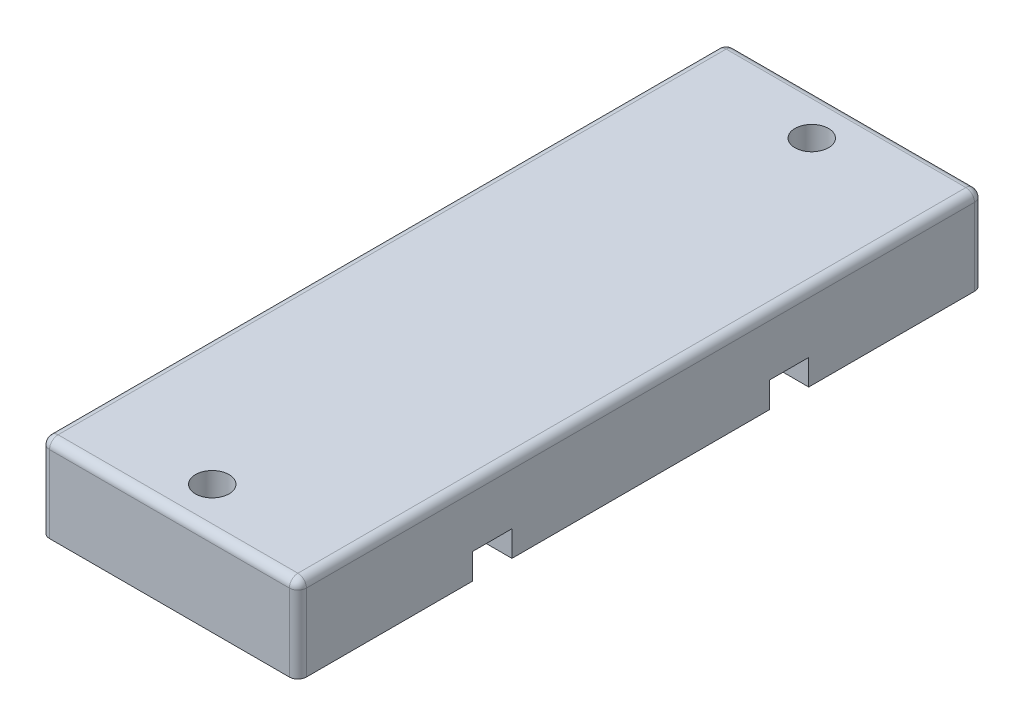
SolidWorks part; units mm, degrees
material "ABS PC"
ref_plane "Front Plane" through (0, 0, 0) normal (0, 0, 1) x (1, 0, 0)
ref_plane "Top Plane" through (0, 0, 0) normal (0, 1, 0) x (1, 0, 0)
ref_plane "Right Plane" through (0, 0, 0) normal (1, 0, 0) x (0, 0, -1)
sketch "Sketch1" plane through (0, 0, 0) normal (0, 1, 0) x (1, 0, 0)
  line L4 (0, 101.6) -> (38.1, 101.6)
  line L5 (0, 101.6) -> (0, 117.8149) construction
  line L6 (38.1, 117.8149) -> (38.1, -40.9351) construction
  line L7 (38.1, 101.6) -> (38.1, 0)
  line L8 (38.1, 0) -> (0, 0)
  line L9 (0, 0) -> (0, 101.6)
extrude "Boss-Extrude1" add sketch "Sketch1" along normal blind 12.7
sketch "Sketch9" plane through (0, 12.7, 0) normal (0, 1, 0) x (1, 0, 0)
  line L0 (19.05, 0) -> (19.05, 6.35) construction
  line L1 (0, 0) -> (38.1, 0) construction
  line L2 (19.05, 101.6) -> (19.05, 95.25) construction
  line L3 (38.1, 101.6) -> (0, 101.6) construction
sketch "Sketch12" plane through (0, 0, 0) normal (-1, 0, 0) x (0, 0, 1)
  line L0 (-101.6, 0) -> (-75.7538, 0) construction
  line L1 (-101.6, 0) -> (0, 0) construction
  line L2 (-75.7538, 0) -> (-69.9156, 0) construction
  line L3 (-69.9156, 0) -> (-31.741, 0) construction
  line L4 (-31.741, 0) -> (-25.9028, 0) construction
  line L5 (-75.7538, 0) -> (-75.7538, 3.81)
  line L6 (-75.7538, 3.81) -> (-69.9156, 3.81)
  line L7 (-69.9156, 3.81) -> (-69.9156, 0)
  line L8 (-69.9156, 0) -> (-75.7538, 0)
  line L9 (-31.741, 0) -> (-31.741, 3.81)
  line L10 (-31.741, 3.81) -> (-25.9028, 3.81)
  line L11 (-25.9028, 3.81) -> (-25.9028, 0)
  line L12 (-25.9028, 0) -> (-31.741, 0)
  dimension "D1" = 5.8383
  dimension "D2" = 5.8383
extrude "Cut-Extrude1" cut sketch "Sketch12" against normal through all
fillet "Fillet2" radius 1.27 8 edges at (38.1, 6.35, -101.6) (38.1, 12.7, -50.8) (38.1, 6.35, 0) (19.05, 12.7, 0) (0, 6.35, 0) (19.05, 12.7, -101.6) (0, 12.7, -50.8) (0, 6.35, -101.6)
sketch "Sketch4" plane through (0, 12.7, 0) normal (0, 1, 0) x (1, 0, 0)
  line L0 (19.05, 0) -> (19.05, 6.35) construction
  line L2 (19.05, 101.6) -> (19.05, 95.25) construction
hole_wizard "#10 (0.1935) Diameter Hole2" positions "Sketch7" profile "Sketch8" hole size "#10" standard "ANSI Inch" end condition through all
sketch "Sketch7" plane through (0, 12.7, 0) normal (0, 1, 0) x (1, 0, 0)
  point P0 (19.05, 95.25)
  point P3 (19.05, 6.35)
sketch "Sketch8" plane through (19.05, 12.7, -95.25) normal (1, 0, 0) x (0, 0, 1)
  line L0 (0, 0) -> (0, 12.7)
  line L1 (0, 12.7) -> (2.4892, 12.7)
  line L2 (2.4892, 12.7) -> (2.4892, 0)
  line L5 (2.4892, 0) -> (0, 0)
  line L11 (0, -6.35) -> (0, 107.95) construction
  dimension "Thru Hole Dia." = 4.9784
  dimension "Thru Hole Depth" = 12.7
